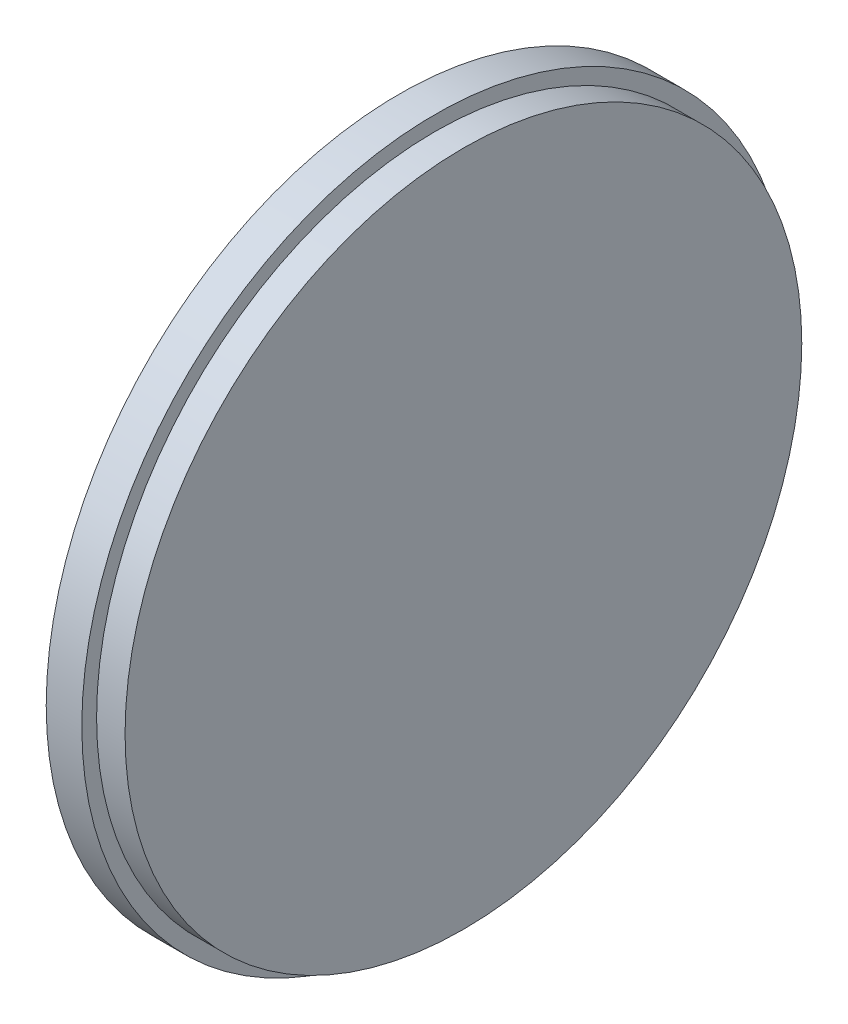
SolidWorks part; units mm, degrees
ref_plane "Front Plane" through (0, 0, 0) normal (0, 0, 1) x (1, 0, 0)
ref_plane "Top Plane" through (0, 0, 0) normal (0, 1, 0) x (1, 0, 0)
ref_plane "Right Plane" through (0, 0, 0) normal (1, 0, 0) x (0, 0, -1)
sketch "Sketch1" plane through (0, 0, 0) normal (1, 0, 0) x (0, 0, -1)
  circle A0 centre (0, 0) radius 32.25
  dimension "D1" = 64.5
extrude "Boss-Extrude1" add sketch "Sketch1" along normal blind 3.25
sketch "Sketch2" plane through (3.25, 0, 0) normal (1, 0, 0) x (0, 0, -1)
  circle A0 centre (0, 0) radius 30.9
  dimension "D1" = 61.8
extrude "Boss-Extrude2" add sketch "Sketch2" along normal blind 2.6
